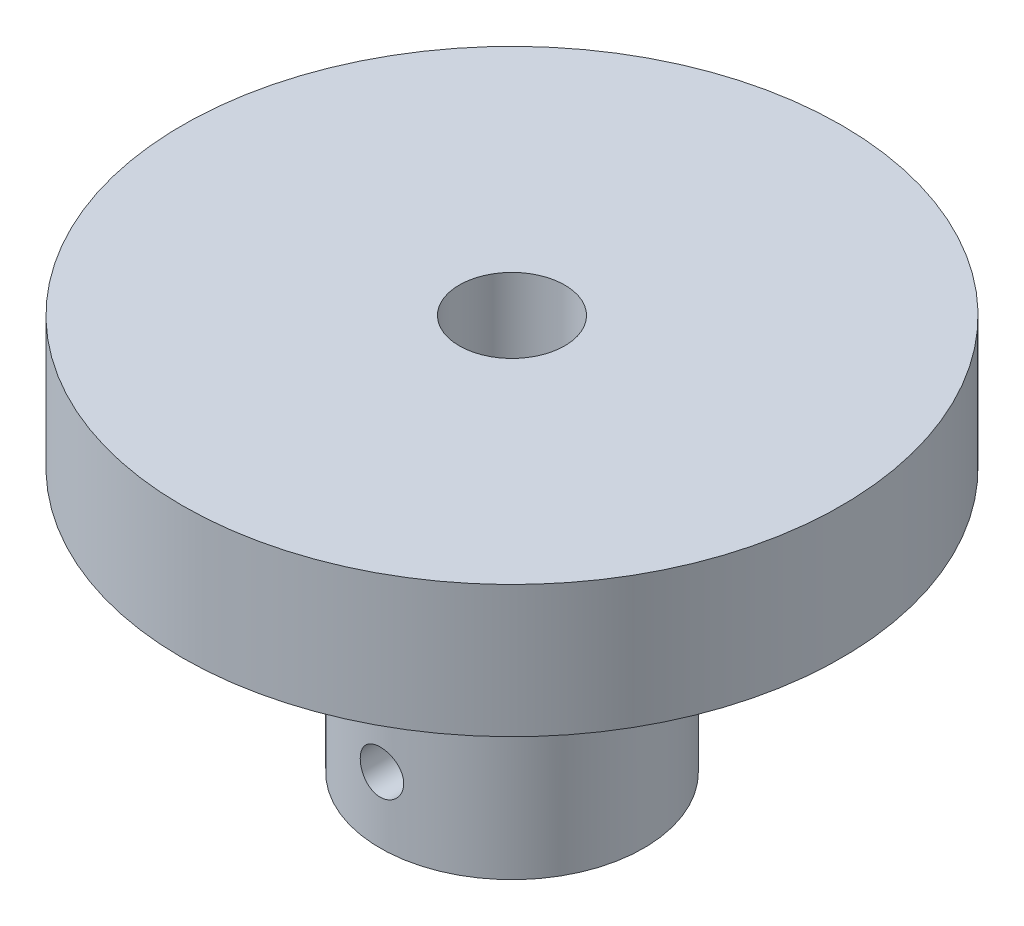
SolidWorks part; units mm, degrees
material "AU4G - 2017A"
ref_plane "Plan de face" through (0, 0, 0) normal (0, 0, 1) x (1, 0, 0)
ref_plane "Plan de dessus" through (0, 0, 0) normal (0, 1, 0) x (1, 0, 0)
ref_plane "Plan de droite" through (0, 0, 0) normal (1, 0, 0) x (0, 0, -1)
sketch "Sketch1" plane through (0, 0, 0) normal (0, 1, 0) x (1, 0, 0)
  circle A0 centre (0, 0) radius 25
  dimension "D1" = 50
extrude "Boss-Extrude1" add sketch "Sketch1" along normal blind 30
sketch "Sketch2" plane through (0, 0, 0) normal (0, -1, 0) x (1, 0, 0)
  circle A0 centre (0, 0) radius 4
  dimension "D1" = 8
extrude "Cut-Extrude1" cut sketch "Sketch2" against normal up to next
sketch "Sketch3" plane through (0, 0, 0) normal (0, -1, 0) x (1, 0, 0)
  circle A0 centre (0, 0) radius 10
  dimension "D1" = 20
extrude "Cut-Extrude2" cut sketch "Sketch3" against normal offset from surface (20 mm away) 10 flip side to cut up to face at (0, 30, 4)
hole_wizard "M4 Tapped Hole1" positions "Sketch5" profile "Sketch4" tap size "M4" standard "DIN"
sketch "Sketch5" plane through (0, 0, 0) normal (0, 0, 1) x (1, 0, 0)
  line L0 (0, 0) -> (0, 5) construction
  point P0 (0, 5)
  point P4 (0, 13)
  dimension "D1" = 5
  dimension "D2" = 8
sketch "Sketch4" plane through (0, 5, 0) normal (1, 0, 0) x (0, 1, 0)
  line L0 (0, 0) -> (0, 10)
  line L1 (0, 10) -> (1.65, 10)
  line L2 (1.65, 10) -> (1.65, 0)
  line L5 (1.65, 0) -> (0, 0)
  line L11 (0, -6.35) -> (0, 107.95) construction
  dimension "Thru Tap Drill Dia." = 3.3
  dimension "Thru Tap Drill Depth" = 10
cosmetic thread "Hole Thread1" parameters "D2"=4
cosmetic thread "Hole Thread2" parameters "D2"=4
chamfer "Chamfer1" distance 1 angle 45 1 edges at (0, 0, -4)
fillet "Fillet1" radius 2 1 edges at (0, 20, 10)
